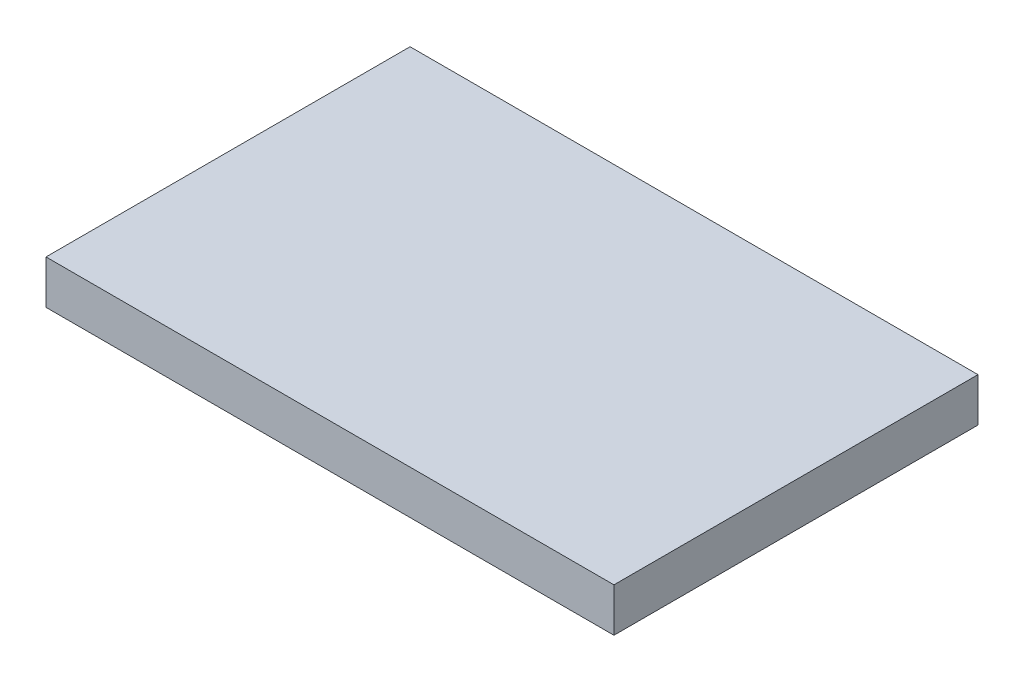
SolidWorks part; units mm, degrees
other "Magic Base"
ref_plane "Front Plane" through (0, 0, 0) normal (0, 0, 1) x (1, 0, 0)
ref_plane "Top Plane" through (0, 0, 0) normal (0, 1, 0) x (1, 0, 0)
ref_plane "Right Plane" through (0, 0, 0) normal (1, 0, 0) x (0, 0, -1)
sketch "Sketch1" plane through (0, 0, 0) normal (0, 1, 0) x (1, 0, 0)
  line L1 (-195, 125) -> (195, 125)
  line L2 (-195, 125) -> (-195, -125)
  line L3 (-195, -125) -> (195, -125)
  line L4 (195, 125) -> (195, -125)
  line L5 (-195, 125) -> (195, -125) construction
  line L6 (-195, -125) -> (195, 125) construction
  point P0 (0, 0)
  dimension "D1" = 390
  dimension "D2" = 250
extrude "Boss-Extrude1" add sketch "Sketch1" along normal blind 30
equation "\"boxWidth\" = 25cm"
equation "\"boxTall\" = 39cm"
equation "\"boxHeight\" = 3cm"
equation "\"DisplayHeight\"= 18mm"
equation "\"DisplayWidth\"= 93mm"
equation "\"DisplayTall\"= 97mm"
